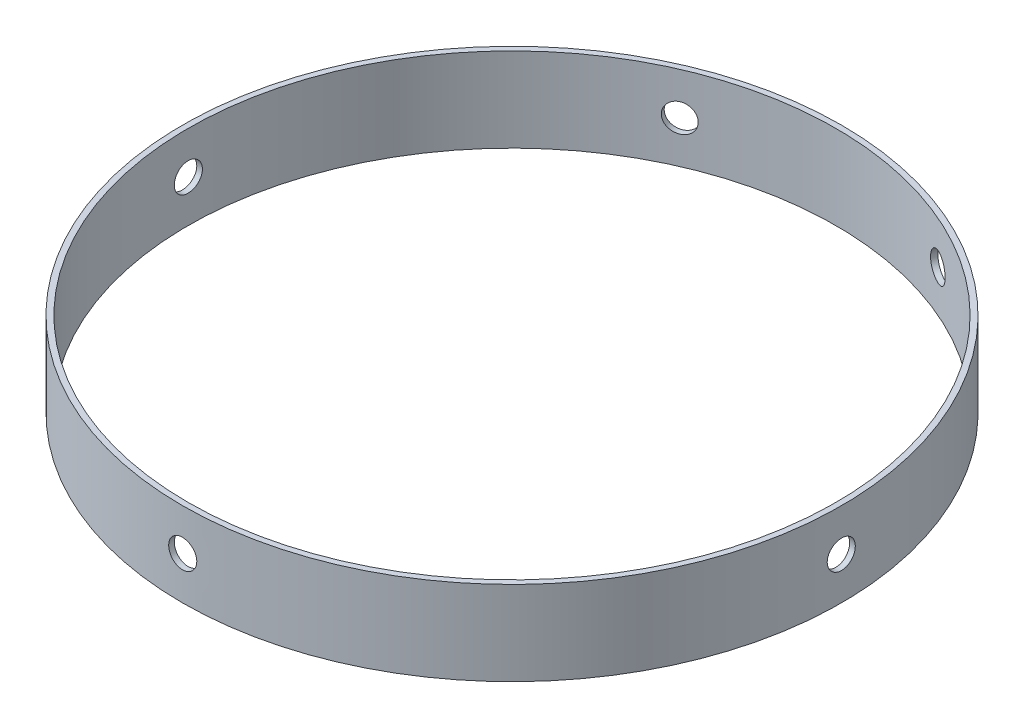
SolidWorks part; units mm, degrees
ref_plane "Front Plane" through (0, 0, 0) normal (0, 0, 1) x (1, 0, 0)
ref_plane "Top Plane" through (0, 0, 0) normal (0, 1, 0) x (1, 0, 0)
ref_plane "Right Plane" through (0, 0, 0) normal (1, 0, 0) x (0, 0, -1)
sketch "Sketch1" plane through (0, 0, 0) normal (0, 1, 0) x (1, 0, 0)
  circle A0 centre (0, 0) radius 74.5363
  circle A1 centre (0, 0) radius 73.2663
  dimension "D1" = 149.0726
  dimension "D2" = 146.5326
extrude "Boss-Extrude1" add sketch "Sketch1" along normal blind 19.05
hole_wizard "1/4 (0.25) Diameter Hole1" positions "3DSketch5" profile "Sketch10" hole size "1/4" standard "ANSI Inch"
sketch3d "3DSketch5"
  line L0 (0, 0, 0) -> (0, 19.05, 0)
  line L1 (0, 19.05, 0) -> (0, 0, 0) construction
  line L9 (0, 9.525, 0) -> (-29.7213, 9.525, -68.3543)
  line L11 (0, 9.525, 0) -> (29.7213, 9.525, -68.3543)
  line L14 (-29.7213, 9.525, -68.3543) -> (29.7213, 9.525, -68.3543) construction
  line L16 (0, 9.525, -68.3543) -> (0, 9.525, 0) construction
  point P0 (-29.7213, 9.525, -68.3543)
  point P2 (29.7213, 9.525, -68.3543)
  point P42 (-29.718, 9.0407, -68.3557)
  dimension "D1" = 47
sketch "Sketch10" plane through (-29.7213, 9.525, -68.3543) normal (0, 1, 0) x (-0.9171, 0, 0.3987)
  line L0 (0, 0) -> (0, 1.27)
  line L1 (0, 1.27) -> (3.175, 1.27)
  line L2 (3.175, 1.27) -> (3.175, 0)
  line L5 (3.175, 0) -> (0, 0)
  line L11 (0, -6.35) -> (0, 107.95) construction
  dimension "Thru Hole Dia." = 6.35
  dimension "Thru Hole Depth" = 1.27
hole_wizard "1/4 (0.25) Diameter Hole4" positions "3DSketch9" profile "Sketch15" hole size "1/4" standard "ANSI Inch"
sketch3d "3DSketch9"
  line L0 (0, 0, 0) -> (0, 19.05, 0) construction
  line L2 (0, 9.525, 0) -> (74.5363, 9.525, 0) construction
  line L3 (0, 19.05, 0) -> (73.2663, 19.05, 0) construction
  line L4 (-74.5363, 9.525, 0) -> (0, 9.525, 0) construction
  line L5 (0, 9.525, 0) -> (0, 9.6744, 74.5363) construction
  circle A3 centre (0, 19.05, 0) radius 73.2663 construction
  point P0 (74.5363, 9.525, 0)
  point P23 (0, 92.3163, 0)
  point P31 (0, 9.6744, 74.5363)
  point P33 (-74.5363, 9.525, 0)
sketch "Sketch15" plane through (74.5363, 9.525, 0) normal (0, 1, 0) x (0, 0, -1)
  line L0 (0, 0) -> (0, 1.27)
  line L1 (0, 1.27) -> (3.175, 1.27)
  line L2 (3.175, 1.27) -> (3.175, 0)
  line L5 (3.175, 0) -> (0, 0)
  line L11 (0, -6.35) -> (0, 107.95) construction
  dimension "Thru Hole Dia." = 6.35
  dimension "Thru Hole Depth" = 1.27
